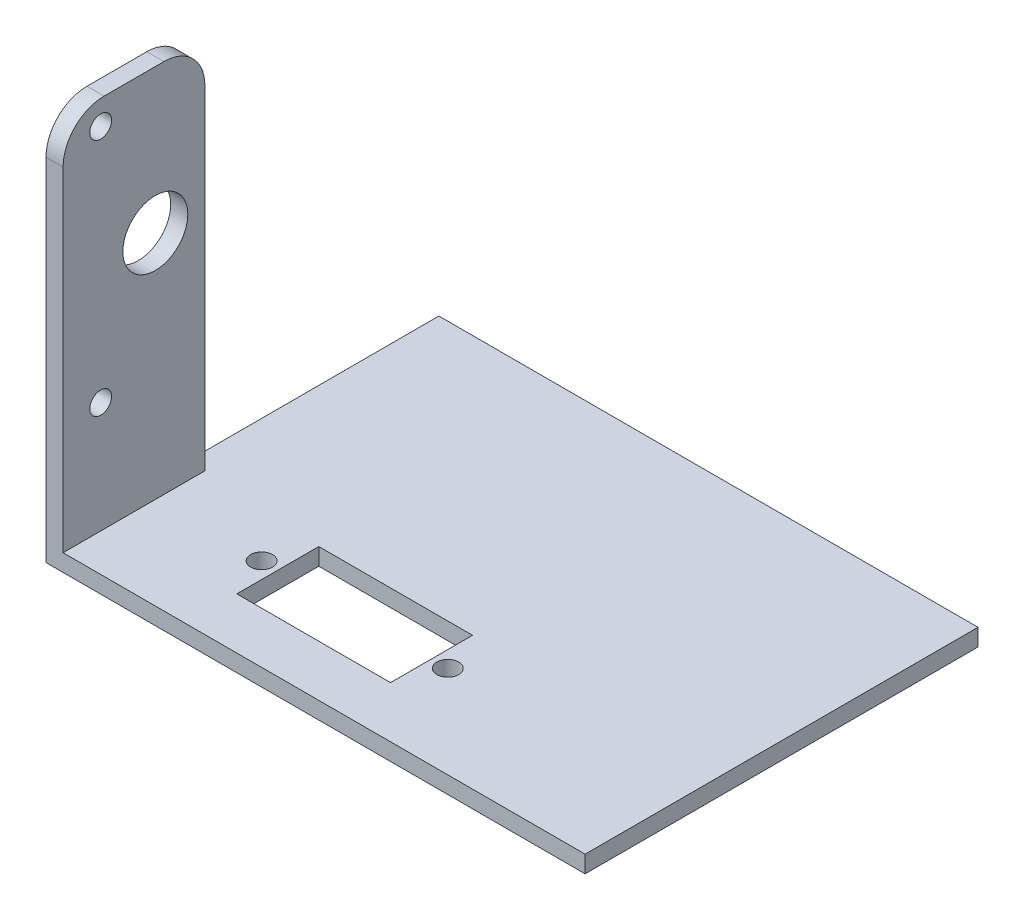
SolidWorks part; units mm, degrees
ref_plane "Front Plane" through (0, 0, 0) normal (0, 0, 1) x (1, 0, 0)
ref_plane "Top Plane" through (0, 0, 0) normal (0, 1, 0) x (1, 0, 0)
ref_plane "Right Plane" through (0, 0, 0) normal (1, 0, 0) x (0, 0, -1)
sketch "Sketch1" plane through (0, 0, 0) normal (0, 1, 0) x (1, 0, 0)
  line L1 (40, -30) -> (-40, -30)
  line L2 (40, -30) -> (40, 30)
  line L3 (40, 30) -> (-40, 30)
  line L4 (-40, -30) -> (-40, 30)
  line L5 (40, -30) -> (-40, 30) construction
  line L6 (40, 30) -> (-40, -30) construction
  point P0 (0, 0)
  dimension "D1" = 80
  dimension "D2" = 60
extrude "Boss-Extrude1" add sketch "Sketch1" along normal blind 2.5 contours L2 L1 L4 L3
sketch "Sketch2" plane through (0, 0, 0) normal (0, 1, 0) x (1, 0, 0)
  line L0 (0, -30) -> (0, -24)
  line L1 (40, -30) -> (-40, -30) construction
  line L2 (-11, -24) -> (21, -24)
  line L3 (-8.625, -24) -> (0, -24)
  line L4 (-11, -24) -> (-6.25, -24)
  line L5 (21, -24) -> (16.25, -24)
  line L6 (16.25, -30) -> (-6.25, -30)
  line L7 (16.25, -30) -> (16.25, -18)
  line L8 (16.25, -18) -> (-6.25, -18)
  line L9 (-6.25, -30) -> (-6.25, -18)
  line L10 (16.25, -30) -> (-6.25, -18) construction
  line L11 (16.25, -18) -> (-6.25, -30) construction
  line L12 (-10.225, -24) -> (0, -24)
  line L13 (-8.625, -24) -> (0, -24)
  circle A2 centre (0, -24) radius 2.5
  circle A3 centre (-8.625, -24) radius 1.6
  circle A4 centre (18.625, -24) radius 1.6
  point P5 (0, -30)
  point P15 (5, -24)
  dimension "D5" = 3.2
  dimension "D7" = 3.2
  dimension "D8" = 5
  dimension "D1" = 6
  dimension "D2" = 11
  dimension "D3" = 32
  dimension "D4" = 4.75
  dimension "D6" = 4.75
  dimension "D9" = 12
  dimension "D10" = 22.5
extrude "Cut-Extrude4" cut sketch "Sketch2" against normal through all and the other way through all contours A2 L2 L7 L8 L9 | A2 L0 L6 L7 L2 | L0 A2 L2 | L2 A2 | L2 A2 L0 | A2 L2 L9 L6 L0 | A3 | A4
sketch "Sketch3" plane through (0, 2.5, 0) normal (0, 1, 0) x (1, 0, 0)
  line L0 (-10.225, -24) -> (0.275, -24)
  line L3 (-40, -30) -> (-37.5, -30)
  line L4 (-40, -30) -> (-40, -9.5)
  line L5 (-40, -9.5) -> (-37.5, -9.5)
  line L6 (-37.5, -30) -> (-37.5, -9.5)
  circle A0 centre (-8.625, -24) radius 1.6 construction
  line M13 (-40, 30) -> (-40, -30)
  line M14 (-40, -30) -> (-6.25, -30)
  dimension "D1" = 10.5
  dimension "D2" = 2.5
  dimension "D3" = 20.5
extrude "Boss-Extrude2" add sketch "Sketch3" along normal blind 66.5 contours L6 L5 M14 M13
sketch "Sketch4" plane through (0, 2.5, 0) normal (0, 1, 0) x (1, 0, 0)
  line L1 (40, -30) -> (-40, -30)
  line L2 (40, -30) -> (40, -35.5)
  line L3 (40, -35.5) -> (-40, -35.5)
  line L4 (-40, -30) -> (-40, -35.5)
  dimension "D1" = 5.5
extrude "Boss-Extrude3" add sketch "Sketch4" against normal up to surface (2.5 mm away) up to face at (18.625, 0, 22.4)
sketch "Sketch5" plane through (0, 2.5, 0) normal (0, 1, 0) x (1, 0, 0)
  line L1 (-37.5, -30) -> (-40, -30)
  line L2 (-37.5, -30) -> (-37.5, -35.5)
  line L3 (-37.5, -35.5) -> (-40, -35.5)
  line L4 (-40, -30) -> (-40, -35.5)
extrude "Boss-Extrude4" add sketch "Sketch5" along normal up to surface (66.5 mm away) up to face at (-38.75, 69, 19.75)
sketch "Sketch6" plane through (0, 69, 0) normal (0, 1, 0) x (1, 0, 0)
  line L0 (-37.5, -35.5) -> (-37.5, -9.5) construction
  line L1 (-40, -9.5) -> (-37.5, -9.5)
  line L2 (-40, -9.5) -> (-40, -15)
  line L3 (-40, -15) -> (-37.5, -15)
  line L4 (-37.5, -9.5) -> (-37.5, -15)
  dimension "D1" = 5.5
extrude "Cut-Extrude5" cut sketch "Sketch6" against normal up to surface (66.5 mm away) up to face at (5, 2.5, 24)
sketch "Sketch7" plane through (0, 2.5, 0) normal (0, 1, 0) x (1, 0, 0)
  line L0 (-10.225, -24) -> (0.275, -24)
  line L1 (15.525, -24) -> (-14.975, -24)
  line L2 (15.525, -24) -> (18.625, -24)
  line L3 (-14.975, -24) -> (-24.175, -24)
  circle A0 centre (-8.625, -24) radius 1.6 construction
  point P8 (0.275, -24)
  dimension "D4" = 9.2
  dimension "D1" = 10.5
  dimension "D2" = 30.5
  dimension "D3" = 3.1
sketch "Sketch9" plane through (0, 2.5, 0) normal (0, 1, 0) x (1, 0, 0)
  line L0 (-10.225, -24) -> (-37.5, -24)
  line L1 (-37.5, -35.5) -> (-37.5, -15) construction
  line L2 (-37.5, -24) -> (-37.5, -35.5)
  line L3 (-37.5, -24) -> (-37.5, -12.5)
  line L4 (-37.5, -12.5) -> (-40, -12.5)
  line L5 (-40, -15) -> (-40, 30) construction
  line L6 (-40, -12.5) -> (-40, -15)
  line L7 (-40, -15) -> (-37.5, -15) construction
  line L8 (-40, -15) -> (-37.5, -15)
  line L9 (-37.5, -15) -> (-37.5, -12.5)
  dimension "D1" = 11.5
extrude "Boss-Extrude5" add sketch "Sketch9" along normal up to surface (66.5 mm away) contours L4 L6 L8 L9 up to face at (-38.75, 69, 25.25)
sketch "Sketch11" plane through (-37.5, 0, 0) normal (1, 0, 0) x (0, 0, -1)
  line L0 (-24, 69) -> (-24, 54)
  line L1 (-35.5, 69) -> (-12.5, 69) construction
  circle A0 centre (-24, 54) radius 4.75
  dimension "D2" = 9.5
  dimension "D1" = 15
extrude "Cut-Extrude6" cut sketch "Sketch11" against normal up to surface (2.5 mm away) contours A0 up to face at (-40, 23.8333, 6)
sketch "Sketch13" plane through (-40, 0, 0) normal (-1, 0, 0) x (0, 0, 1)
  line L0 (24, 54) -> (32, 54)
  line L1 (32, 36.5) -> (32, 71.5)
  point P7 (32, 54)
  dimension "D1" = 8
  dimension "D2" = 35
sketch "Sketch15" plane through (0, 69, 0) normal (0, 1, 0) x (1, 0, 0)
  line L1 (-40, -12.5) -> (-37.5, -12.5)
  line L2 (-40, -12.5) -> (-40, -35.5)
  line L3 (-40, -35.5) -> (-37.5, -35.5)
  line L4 (-37.5, -12.5) -> (-37.5, -35.5)
extrude "Boss-Extrude6" add sketch "Sketch15" along normal blind 8
sketch "Sketch17" plane through (0, 0, 35.5) normal (0, 0, 1) x (1, 0, 0)
  line L1 (-40, 77) -> (-37.5, 77)
  line L2 (-40, 77) -> (-40, 2.5)
  line L3 (-40, 2.5) -> (-37.5, 2.5)
  line L4 (-37.5, 77) -> (-37.5, 2.5)
extrude "Boss-Extrude7" add sketch "Sketch17" along normal blind 2
sketch "Sketch18" plane through (-40, 0, 0) normal (-1, 0, 0) x (0, 0, 1)
  circle A0 centre (32, 36.5) radius 1.6
  circle A1 centre (32, 71.5) radius 1.6
  dimension "D1" = 3.2
  dimension "D2" = 3.2
extrude "Cut-Extrude7" cut sketch "Sketch18" against normal up to surface (2.5 mm away) up to face at (-37.5, 54, 19.25)
sketch "Sketch21" plane through (0, 0, 35.5) normal (0, 0, 1) x (1, 0, 0)
  line L1 (-40, 2.5) -> (40, 2.5)
  line L2 (-40, 2.5) -> (-40, 0)
  line L3 (-40, 0) -> (40, 0)
  line L4 (40, 2.5) -> (40, 0)
extrude "Boss-Extrude8" add sketch "Sketch21" along normal up to surface (2 mm away) up to face at (-38.75, 39.75, 37.5)
sketch "Sketch22" plane through (-37.5, 0, 0) normal (1, 0, 0) x (0, 0, -1)
  line L0 (-37.5, 2.5) -> (-12.5, 2.5) construction
  line L1 (-12.5, 77) -> (-16.75, 77)
  line L2 (-12.5, 77) -> (-12.5, 2.5)
  line L3 (-12.5, 2.5) -> (-16.75, 2.5)
  line L4 (-16.75, 77) -> (-16.75, 2.5)
  dimension "D1" = 4.25
extrude "Cut-Extrude8" cut sketch "Sketch22" against normal up to surface (2.5 mm away) up to face at (-40, 36.5, 33.6)
fillet "Fillet1" radius 5 2 edges at (-38.75, 77, 16.75) (-38.75, 77, 37.5)
sketch "Sketch23" plane through (0, 2.5, 0) normal (0, 1, 0) x (1, 0, 0)
  line L0 (20.225, -24) -> (55.225, -24)
  line L1 (40, 30) -> (40, -37.5)
  line L6 (40, -37.5) -> (55.225, -37.5)
  line L7 (55.225, -37.5) -> (55.225, 30)
  line L8 (55.225, 30) -> (40, 30)
  circle A0 centre (18.625, -24) radius 1.6 construction
  dimension "D1" = 35
extrude "Boss-Extrude10" add sketch "Sketch23" against normal up to surface (2.5 mm away) contours L8 L1 L6 L7 up to face at (0, 0, 3.75)
sketch "Sketch24" plane through (0, 2.5, 0) normal (0, 1, 0) x (1, 0, 0)
  line L0 (55.225, -37.5) -> (55.225, 30) construction
  line L1 (-40, 30) -> (55.225, 30)
  line L2 (-40, 30) -> (-40, 20)
  line L3 (-40, 20) -> (55.225, 20)
  line L4 (55.225, 30) -> (55.225, 20)
  dimension "D1" = 10
extrude "Cut-Extrude9" cut sketch "Sketch24" against normal through all
sketch "Sketch26" plane through (0, 2.5, 0) normal (0, 1, 0) x (1, 0, 0)
  line L0 (-24.175, -37.5) -> (-24.175, -16.75)
  line L1 (55.225, -37.5) -> (-37.5, -37.5) construction
  line L2 (-24.175, -16.75) -> (-26.675, -16.75)
  line L3 (-26.675, -16.75) -> (-26.675, -37.5)
  line L4 (-26.675, -37.5) -> (-24.175, -37.5)
extrude "Boss-Extrude11" add sketch "Sketch26" along normal up to surface (74.5 mm away) up to face at (-38.75, 77, 27.125)
sketch "Sketch27" plane through (-24.175, 0, 0) normal (1, 0, 0) x (0, 0, -1)
  line L0 (-24, 2.5) -> (-24, 36.275)
  line L2 (-24, 36.275) -> (-32, 36.275)
  line L4 (-32, 18.775) -> (-32, 53.775)
  circle A0 centre (-24, 36.275) radius 4.75
  circle A1 centre (-32, 53.775) radius 1.6
  circle A2 centre (-32, 18.775) radius 1.6
  point P4 (-32, 36.275)
  dimension "D2" = 9.5
  dimension "D5" = 3.2
  dimension "D6" = 3.2
  dimension "D1" = 33.775
  dimension "D3" = 8
  dimension "D4" = 35
extrude "Cut-Extrude10" cut sketch "Sketch27" against normal up to surface (2.5 mm away) contours L0 A0 L2 | L2 A0 L0 | A2 | A1 up to face at (-26.675, 39.75, 27.125)
sketch "Sketch28" plane through (0, 77, 0) normal (0, 1, 0) x (1, 0, 0)
  line L1 (-40, -16.75) -> (-37.5, -16.75)
  line L2 (-40, -16.75) -> (-40, -37.5)
  line L3 (-40, -37.5) -> (-37.5, -37.5)
  line L4 (-37.5, -16.75) -> (-37.5, -37.5)
extrude "Cut-Extrude11" cut sketch "Sketch28" against normal up to surface (74.5 mm away) up to face at (5, 2.5, 24)
sketch "Sketch29" plane through (-24.175, 0, 0) normal (1, 0, 0) x (0, 0, -1)
  line L0 (-32, 55.375) -> (-32, 57.375)
  line L1 (-32, 36.5) -> (-32, 71.5) construction
  line L2 (-16.75, 77) -> (-16.75, 2.5) construction
  line L3 (-37.5, 77) -> (-16.75, 77)
  line L4 (-37.5, 77) -> (-37.5, 57.375)
  line L5 (-37.5, 57.375) -> (-16.75, 57.375)
  line L6 (-16.75, 77) -> (-16.75, 57.375)
  circle A0 centre (-32, 53.775) radius 1.6 construction
  dimension "D1" = 2
extrude "Cut-Extrude12" cut sketch "Sketch29" against normal up to surface (2.5 mm away) contours L4 L3 L6 L5 up to face at (-26.675, 36.275, 19.25)
fillet "Fillet2" radius 6 2 edges at (-25.425, 57.375, 16.75) (-25.425, 57.375, 37.5)
sketch "Sketch31" plane through (0, 2.5, 0) normal (0, 1, 0) x (1, 0, 0)
  line L1 (-40, 20) -> (-26.675, 20)
  line L2 (-40, 20) -> (-40, -37.5)
  line L3 (-40, -37.5) -> (-26.675, -37.5)
  line L4 (-26.675, 20) -> (-26.675, -37.5)
extrude "Cut-Extrude13" cut sketch "Sketch31" against normal up to surface (2.5 mm away) up to face at (7.6125, 0, 8.75)
sketch "Sketch33" plane through (0, 2.5, 0) normal (0, 1, 0) x (1, 0, 0)
  line L0 (55.225, -37.5) -> (-24.175, -37.5) construction
  line L1 (55.225, 20) -> (52.225, 20)
  line L2 (55.225, 20) -> (55.225, -37.5)
  line L3 (55.225, -37.5) -> (52.225, -37.5)
  line L4 (52.225, 20) -> (52.225, -37.5)
  dimension "D1" = 3
extrude "Cut-Extrude14" cut sketch "Sketch33" against normal up to surface (2.5 mm away) up to face at (14.275, 0, 8.75)
